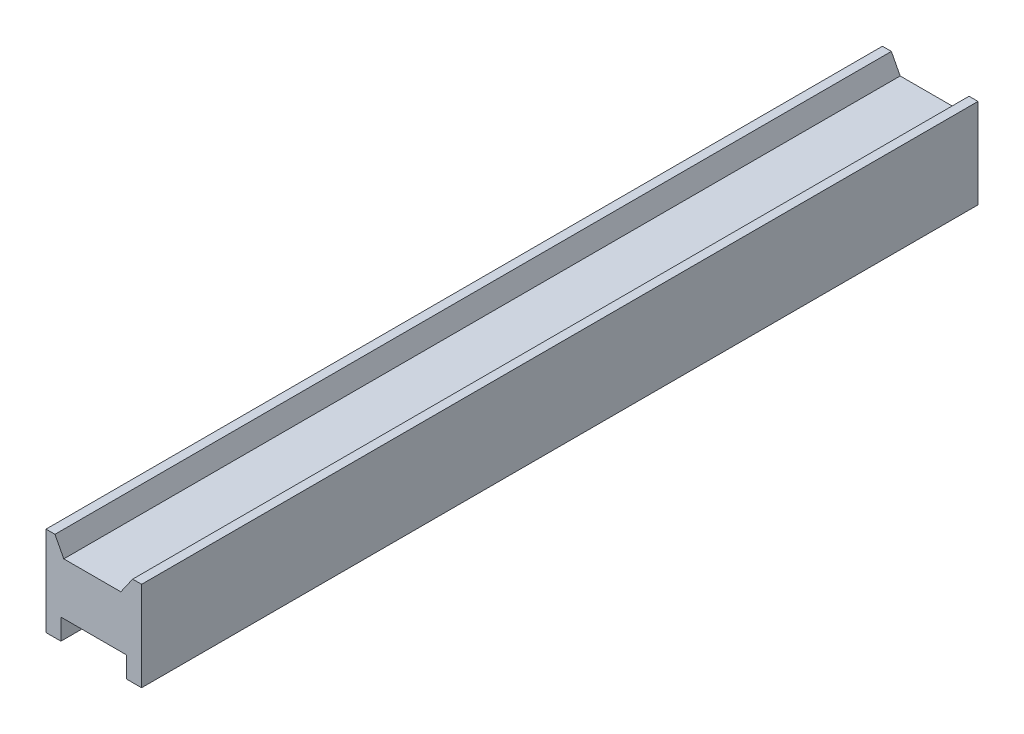
SolidWorks part; units mm, degrees
ref_plane "Alzado" through (0, 0, 0) normal (0, 0, 1) x (1, 0, 0)
ref_plane "Planta" through (0, 0, 0) normal (0, 1, 0) x (1, 0, 0)
ref_plane "Vista lateral" through (0, 0, 0) normal (1, 0, 0) x (0, 0, -1)
sketch "Croquis1" plane through (0, 0, 0) normal (0, 0, 1) x (1, 0, 0)
  line L0 (0, 0) -> (0, 1500)
  line L1 (0, 0) -> (250, 0)
  line L2 (250, 0) -> (250, 350)
  line L3 (250, 350) -> (1350, 350)
  line L4 (1350, 350) -> (1350, 0)
  line L5 (1350, 0) -> (1600, 0)
  line L6 (1600, 0) -> (1600, 1500)
  line L7 (1600, 1500) -> (1450, 1500)
  line L8 (1450, 1500) -> (1252.2308, 1217.5564)
  line L9 (1252.2308, 1217.5564) -> (297.6927, 1217.5564)
  line L10 (297.6927, 1217.5564) -> (150, 1500)
  line L11 (150, 1500) -> (0, 1500)
  dimension "D1" = 1500
  dimension "D2" = 250
  dimension "D3" = 350
  dimension "D4" = 1100
  dimension "D5" = 250
  dimension "D6" = 150
  dimension "D7" = 150
  dimension "D8" = 125
extrude "Saliente-Extruir1" add sketch "Croquis1" along normal blind 14000
